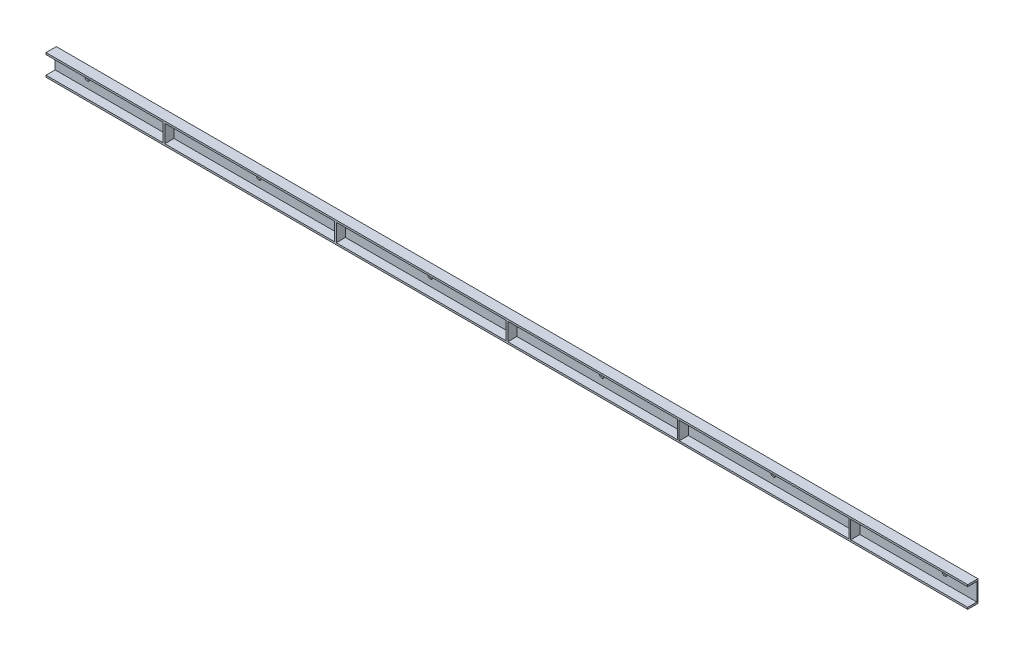
SolidWorks part; units mm, degrees
ref_plane "前视基准面" through (0, 0, 0) normal (0, 0, 1) x (1, 0, 0)
ref_plane "上视基准面" through (0, 0, 0) normal (0, 1, 0) x (1, 0, 0)
ref_plane "右视基准面" through (0, 0, 0) normal (1, 0, 0) x (0, 0, -1)
sketch "草图1" plane through (0, 0, 0) normal (0, 0, 1) x (1, 0, 0)
  line L1 (0, 0) -> (4300, 0)
  line L2 (0, 0) -> (0, 100)
  line L3 (0, 100) -> (4300, 100)
  line L4 (4300, 0) -> (4300, 100)
  dimension "D1" = 4300
  dimension "D2" = 100
extrude "拉伸1" add sketch "草图1" along normal blind 48
sketch "草图2" plane through (0, 0, 48) normal (0, 0, 1) x (1, 0, 0)
  line L0 (0, 100) -> (0, 0) construction
  line L1 (0, 91.5) -> (4300, 91.5)
  line L2 (0, 91.5) -> (0, 8.5)
  line L3 (0, 8.5) -> (4300, 8.5)
  line L4 (4300, 91.5) -> (4300, 8.5)
  line L5 (4300, 100) -> (0, 100) construction
  line L6 (0, 0) -> (4300, 0) construction
  line L7 (4300, 0) -> (4300, 100) construction
  dimension "D1" = 8.5
  dimension "D2" = 8.5
extrude "拉伸2" cut sketch "草图2" against normal blind 42.7
sketch "草图3" plane through (0, 0, 5.3) normal (0, 0, 1) x (1, 0, 0)
  line L0 (4300, 91.5) -> (0, 91.5) construction
  line L1 (545.75, 91.5) -> (554.25, 91.5)
  line L2 (545.75, 91.5) -> (545.75, 8.5)
  line L3 (545.75, 8.5) -> (554.25, 8.5)
  line L4 (554.25, 91.5) -> (554.25, 8.5)
  line L5 (0, 8.5) -> (4300, 8.5) construction
  line L6 (550, 91.5) -> (550, 8.5) construction
  line L7 (0, 91.5) -> (0, 8.5) construction
  dimension "D1" = 8.5
  dimension "D2" = 550
extrude "拉伸3" add sketch "草图3" along normal blind 42.7
pattern_linear "阵列(线性)1" count 5 spacing 800 along (1, 0, 0) of "拉伸3"
sketch "草图4" plane through (0, 0, 0) normal (0, 0, -1) x (-1, 0, 0)
  line L0 (-4300, 50) -> (0, 50) construction
  line L1 (-4300, 0) -> (-4300, 100) construction
  line L2 (0, 100) -> (0, 0) construction
  circle A0 centre (-4150, 50) radius 11.5
  dimension "D1" = 23
  dimension "D2" = 150
extrude "拉伸4" cut sketch "草图4" against normal through all
pattern_linear "阵列(线性)2" count 6 spacing 800 along (-1, 0, 0) of "拉伸4"
